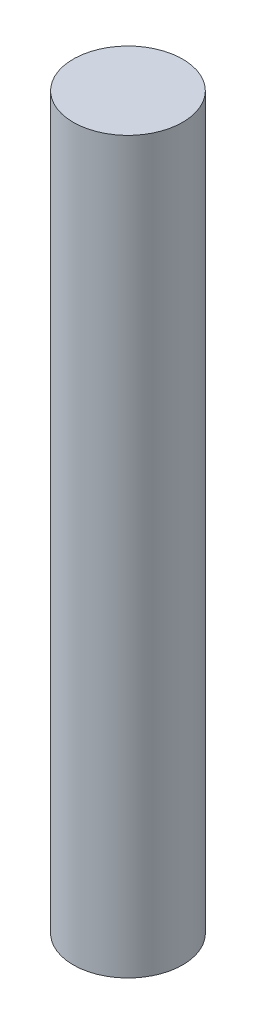
SolidWorks part; units mm, degrees
ref_plane "Front Plane" through (0, 0, 0) normal (0, 0, 1) x (1, 0, 0)
ref_plane "Top Plane" through (0, 0, 0) normal (0, 1, 0) x (1, 0, 0)
ref_plane "Right Plane" through (0, 0, 0) normal (1, 0, 0) x (0, 0, -1)
sketch "Sketch1" plane through (0, 0, 0) normal (0, 1, 0) x (1, 0, 0)
  circle A0 centre (0, 0) radius 1.5
  dimension "D1" = 1.5
extrude "Boss-Extrude1" add sketch "Sketch1" along normal blind 20
equation "\"N_pins\"= 26"
equation "\"N_lobes\"= \"N_pins\" - 1"
equation "\"R_pc\"= 25"
equation "\"D_pin\"= 3"
equation "\"R_pin\"= \"D_pin\" / 2"
equation "\"ecc\"= 0.72"
equation "\"t_disc\"= 7"
equation "\"N_out\"= 8"
equation "\"D_outc\"=22"
equation "\"D_roller\"= 5"
equation "\"D_outhole\"= \"D_roller\" + 2 * \"ecc\""
equation "\"D_cam_OD\"= 21"
equation "\"D_cam_ID\"= 10"
equation "\"clr_bore\"= 1"
equation "\"D_bore\"= 2 * \"R_pc\" + \"clr_bore\""
equation "\"t_wall\"= 7.5"
equation "\"D_housing\"= \"D_bore\" + 2 * \"t_wall\""
equation "\"D1@Sketch1\"=\"R_pin\""
